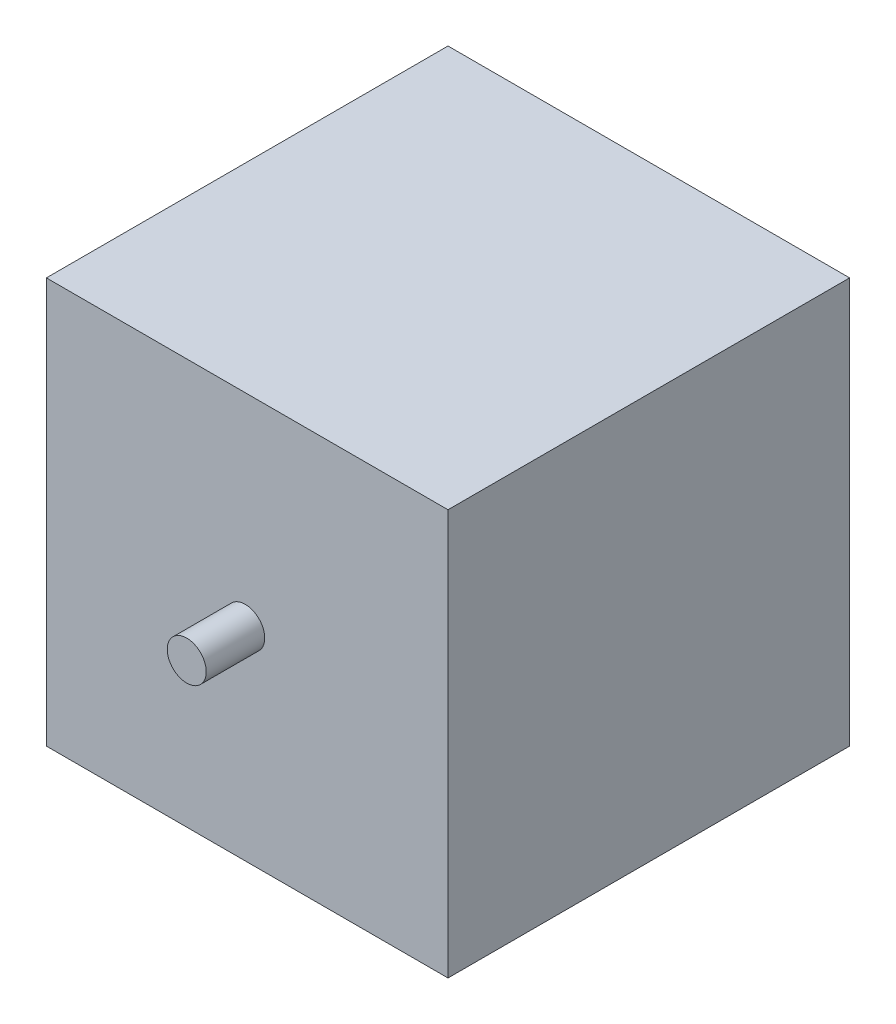
SolidWorks part; units mm, degrees
ref_plane "Front Plane" through (0, 0, 0) normal (0, 0, 1) x (1, 0, 0)
ref_plane "Top Plane" through (0, 0, 0) normal (0, 1, 0) x (1, 0, 0)
ref_plane "Right Plane" through (0, 0, 0) normal (1, 0, 0) x (0, 0, -1)
sketch "Sketch1" plane through (0, 0, 0) normal (0, 1, 0) x (1, 0, 0)
  line L1 (-51.5, -51.5) -> (51.5, -51.5)
  line L2 (-51.5, -51.5) -> (-51.5, 51.5)
  line L3 (-51.5, 51.5) -> (51.5, 51.5)
  line L4 (51.5, -51.5) -> (51.5, 51.5)
  line L5 (-51.5, -51.5) -> (51.5, 51.5) construction
  line L6 (-51.5, 51.5) -> (51.5, -51.5) construction
  point P0 (0, 0)
  dimension "D1" = 103
  dimension "D2" = 103
extrude "Boss-Extrude1" add sketch "Sketch1" along normal blind 104
sketch "Sketch2" plane through (0, 0, 51.5) normal (0, 0, 1) x (1, 0, 0)
  line L0 (51.5, 104) -> (51.5, 0) construction
  circle A0 centre (-0.5, 51.9976) radius 5
  dimension "D1" = 10
  dimension "D2" = 52
  dimension "D3" = 52
extrude "Boss-Extrude2" add sketch "Sketch2" along normal blind 15
sketch "Sketch3" plane through (0, 0, -51.5) normal (0, 0, -1) x (-1, 0, 0)
  line L0 (-51.5, 104) -> (-51.5, 0) construction
  circle A0 centre (0.5, 51.9976) radius 5
  dimension "D1" = 10
  dimension "D2" = 52
  dimension "D3" = 52
extrude "Boss-Extrude3" add sketch "Sketch3" along normal blind 15
sketch "Sketch4" plane through (-51.5, 0, 0) normal (-1, 0, 0) x (0, 0, 1)
  circle A0 centre (0, 52) radius 12.5
  circle A1 centre (0, 52) radius 17.5
  dimension "D1" = 25
  dimension "D2" = 35
extrude "Cut-Extrude1" cut sketch "Sketch4" against normal blind 20
